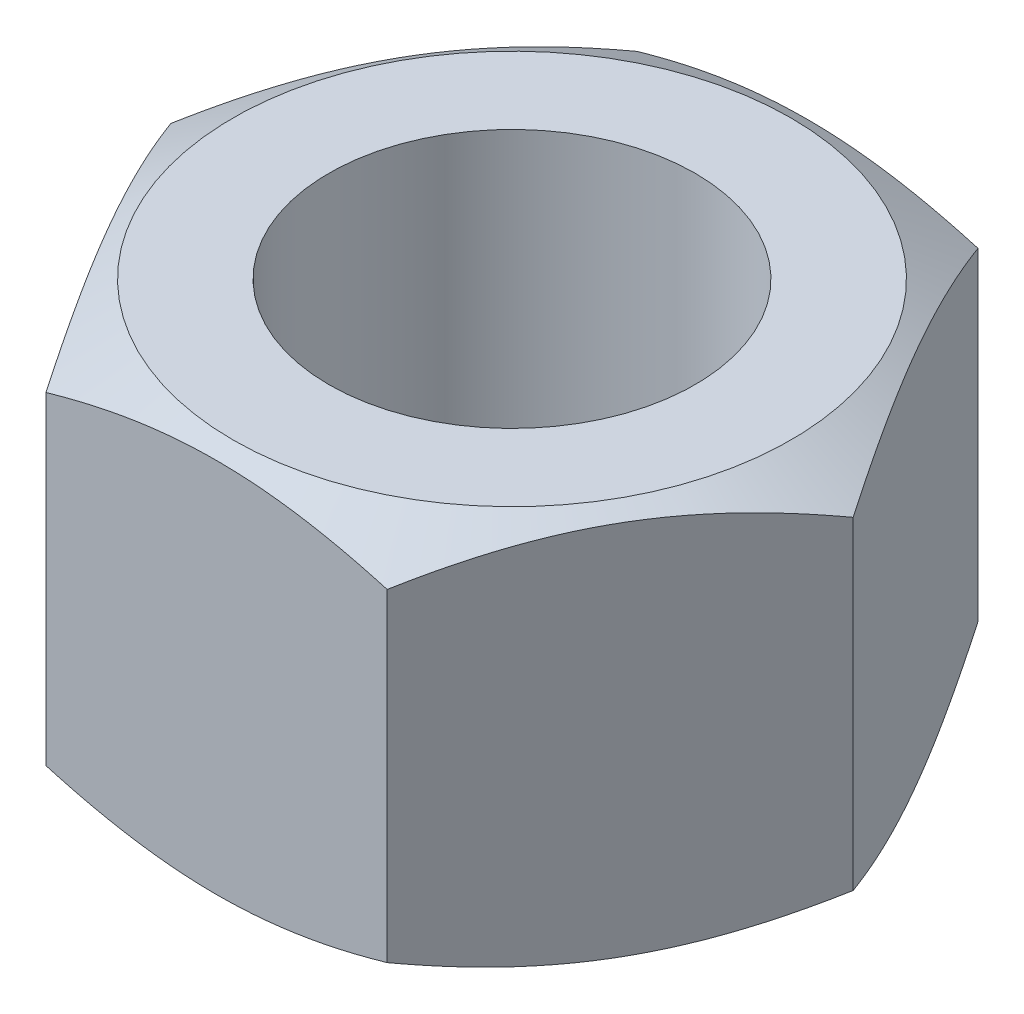
SolidWorks part; units mm, degrees
ref_plane "前视基准面" through (0, 0, 0) normal (0, 0, 1) x (1, 0, 0)
ref_plane "上视基准面" through (0, 0, 0) normal (0, 1, 0) x (1, 0, 0)
ref_plane "右视基准面" through (0, 0, 0) normal (1, 0, 0) x (0, 0, -1)
sketch "草图1" plane through (0, 0, 0) normal (0, 1, 0) x (1, 0, 0)
  line L1 (9.5, 0) -> (4.75, 8.2272)
  line L2 (4.75, 8.2272) -> (-4.75, 8.2272)
  line L3 (-4.75, 8.2272) -> (-9.5, 0)
  line L4 (-9.5, 0) -> (-4.75, -8.2272)
  line L5 (-4.75, -8.2272) -> (4.75, -8.2272)
  line L6 (4.75, -8.2272) -> (9.5, 0)
  circle A0 centre (0, 0) radius 8.2272 construction
  dimension "D1" = 19
extrude "凸台-拉伸1" add sketch "草图1" along normal blind 11
sketch "草图2" plane through (0, 11, 0) normal (0, 1, 0) x (1, 0, 0)
  point P0 (0, 0)
hole_wizard "M12 螺纹孔1" positions "草图2" profile "草图3" tap size "M12" standard "GB" end condition up to next
sketch "草图3" plane through (0, 11, 0) normal (1, 0, 0) x (0, 0, 1)
  line L0 (0, 0) -> (0, 11)
  line L1 (0, 11) -> (5.1, 11)
  line L2 (5.1, 11) -> (5.1, 0)
  line L5 (5.1, 0) -> (0, 0)
  line L11 (0, -6.35) -> (0, 107.95) construction
  dimension "通孔螺纹孔钻头直径" = 10.2
  dimension "通孔螺纹孔钻头深度" = 11
cosmetic thread "孔螺纹线1" parameters "D2"=12
sketch "草图4" plane through (0, 0, 0) normal (0, 0, 1) x (1, 0, 0)
  line L0 (-9.5, 10) -> (-7.7679, 11)
  line L1 (-9.5, 11) -> (-9.5, 0) construction
  line L2 (-9.5, 11) -> (-4.75, 11) construction
  line L3 (0, 0) -> (0, 14.0207) construction
  line L4 (-9.5, 10) -> (-9.5, 11)
  line L5 (-9.5, 11) -> (-7.7679, 11)
  dimension "D1" = 30
  dimension "D2" = 1
revolve "切除-旋转1" cut sketch "草图4" angle 360 about L3
ref_plane "基准面4" through (0, 5.5, 0) normal (0, 1, 0) x (1, 0, 0)
mirror "镜向1" about plane through (0, 5.5, 0) normal (0, 1, 0) of "切除-旋转1"
